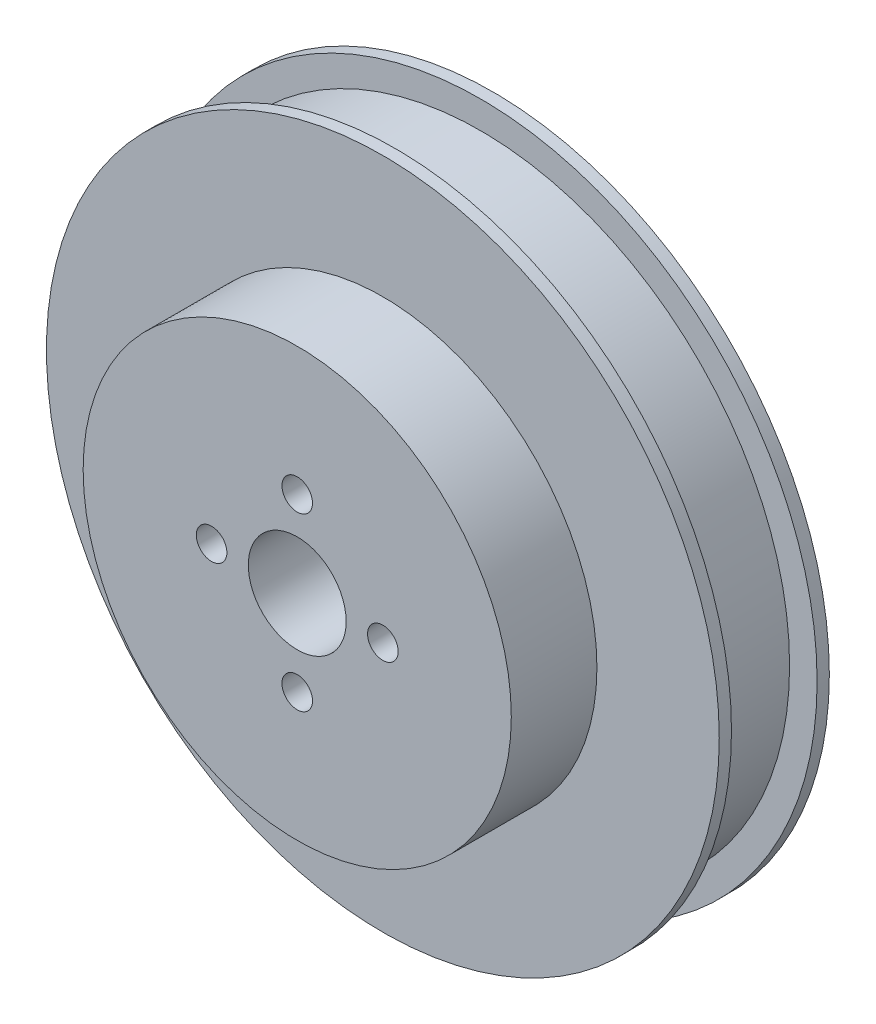
SolidWorks part; units mm, degrees
ref_plane "前视基准面" through (0, 0, 0) normal (0, 0, 1) x (1, 0, 0)
ref_plane "上视基准面" through (0, 0, 0) normal (0, 1, 0) x (1, 0, 0)
ref_plane "右视基准面" through (0, 0, 0) normal (1, 0, 0) x (0, 0, -1)
sketch "草图1" plane through (0, 0, 0) normal (0, 0, 1) x (1, 0, 0)
  circle A0 centre (0, 0) radius 27.5
  dimension "D1" = 55
extrude "凸台-拉伸1" add sketch "草图1" along normal blind 1
sketch "草图2" plane through (0, 0, 1) normal (0, 0, 1) x (1, 0, 0)
  circle A0 centre (0, 0) radius 25.25
  dimension "D1" = 50.5
extrude "凸台-拉伸2" add sketch "草图2" along normal blind 7
sketch "草图3" plane through (0, 0, 8) normal (0, 0, 1) x (1, 0, 0)
  circle A0 centre (0, 0) radius 27.5
extrude "凸台-拉伸3" add sketch "草图3" along normal blind 1
sketch "草图4" plane through (0, 0, 9) normal (0, 0, 1) x (1, 0, 0)
  circle A0 centre (0, 0) radius 17.5
  dimension "D1" = 35
extrude "凸台-拉伸4" add sketch "草图4" along normal blind 7
sketch "草图5" plane through (0, 0, 16) normal (0, 0, 1) x (1, 0, 0)
  circle A0 centre (0, 0) radius 4
  dimension "D1" = 8
extrude "切除-拉伸1" cut sketch "草图5" against normal blind 100
sketch "草图6" plane through (0, 0, 0) normal (0, 0, -1) x (-1, 0, 0)
  circle A0 centre (7, 0) radius 1.25
  circle A1 centre (0, -7) radius 1.25
  circle A2 centre (-7, 0) radius 1.25
  circle A3 centre (0, 7) radius 1.25
  dimension "D1" = 2.5
  dimension "D2" = 7
  dimension "D3" = 4
extrude "切除-拉伸2" cut sketch "草图6" against normal blind 100
